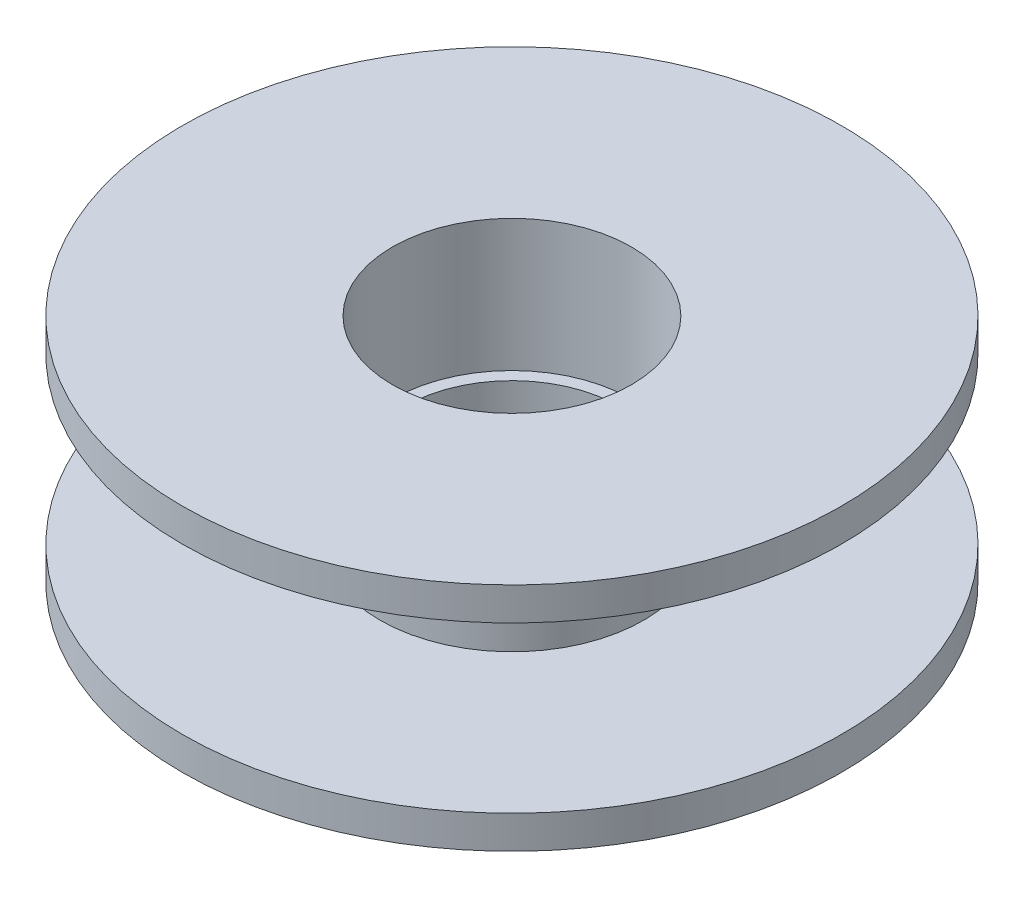
SolidWorks part; units mm, degrees
ref_plane "Front Plane" through (0, 0, 0) normal (0, 0, 1) x (1, 0, 0)
ref_plane "Top Plane" through (0, 0, 0) normal (0, 1, 0) x (1, 0, 0)
ref_plane "Right Plane" through (0, 0, 0) normal (1, 0, 0) x (0, 0, -1)
sketch "Sketch1" plane through (0, 0, 0) normal (1, 0, 0) x (0, 0, -1)
  line L0 (0, 28.0586) -> (0, -24.3494) construction
  line L5 (-16, 9.8387) -> (-40, 9.8387)
  line L6 (-40, 9.8387) -> (-40, 5.8387)
  line L7 (-40, 5.8387) -> (-13, 5.8387)
  line L8 (-13, 5.8387) -> (-13, 17.8387)
  line L14 (-16, 9.8387) -> (-16, 29.8387)
  line L15 (-16, 29.8387) -> (-14.5, 29.8387)
  line L16 (-14.5, 29.8387) -> (-14.5, 17.8387)
  line L17 (-13, 17.8387) -> (-14.5, 17.8387)
  dimension "D1" = 29
  dimension "D2" = 26
  dimension "D3" = 12
  dimension "D4" = 20
  dimension "D5" = 4
  dimension "D6" = 32
  dimension "D7" = 80
revolve "Revolve1" add sketch "Sketch1" angle 360 about L0
ref_plane "Plane1" through (0, 19.8387, 0) normal (0, 1, 0) x (1, 0, 0)
mirror "Mirror3" about plane through (0, 19.8387, 0) normal (0, 1, 0) of "Revolve1"
sketch "Sketch2" plane through (0, 17.8387, 0) normal (0, 1, 0) x (1, 0, 0)
  circle A0 centre (0, 0) radius 14.5
extrude "Cut-Extrude1" cut sketch "Sketch2" along normal blind 48
